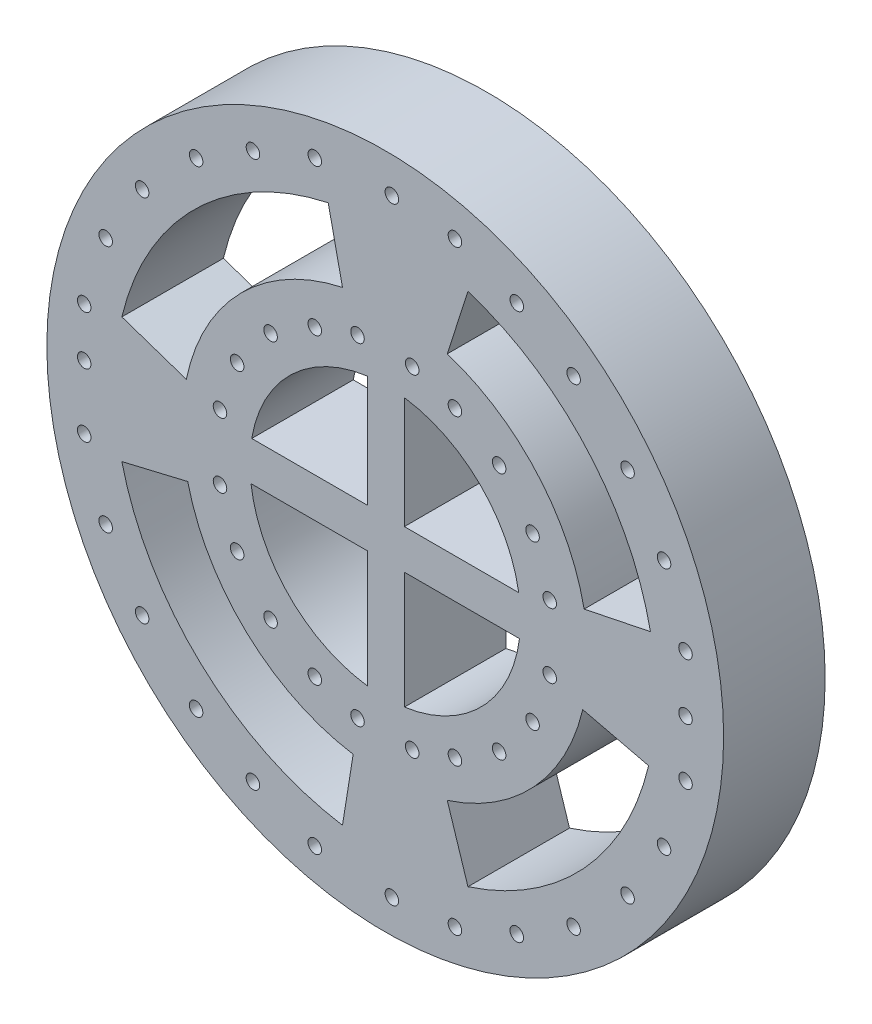
SolidWorks part; units mm, degrees
ref_plane "Front Plane" through (0, 0, 0) normal (0, 0, 1) x (1, 0, 0)
ref_plane "Top Plane" through (0, 0, 0) normal (0, 1, 0) x (1, 0, 0)
ref_plane "Right Plane" through (0, 0, 0) normal (1, 0, 0) x (0, 0, -1)
sketch "Sketch1" plane through (0, 0, 0) normal (0, 0, 1) x (1, 0, 0)
  line L0 (-26.585, -3.3326) -> (-26.585, 40.517)
  line L1 (-40.3947, -3.4074) -> (-40.3947, 40.517)
  line L2 (65.0807, 23.4507) -> (40.3699, 29.3275)
  line L3 (65.7686, 67.3569) -> (40.8858, 62.2571)
  line L4 (-10.4829, 119.5147) -> (-2.723, 143.7003)
  line L5 (-107.8949, 29.3275) -> (-132.6057, 23.4507)
  line L6 (16.3433, 55.3276) -> (-26.585, 55.3276)
  line L7 (-49.8085, -53.3671) -> (-45.797, -28.2859)
  line L8 (-2.723, -49.7847) -> (-10.4829, -25.5991)
  line L9 (-108.4108, 62.2571) -> (-132.6057, 70.4649)
  line L10 (-49.8085, 121.4492) -> (-55.1572, 146.2796)
  line L11 (-84.1525, 40.517) -> (-40.3947, 40.517)
  line L12 (-26.585, 40.517) -> (16.6276, 40.517)
  line L13 (-40.3947, 55.3276) -> (-83.8682, 55.3276)
  line L14 (-26.585, 55.3276) -> (-26.585, 97.2482)
  line L15 (-40.3947, 55.3276) -> (-40.3947, 97.323)
  circle A0 centre (-33.7625, 46.9578) radius 127
  arc A1 (65.7686, 67.3569) -> (-2.723, 143.7003) centre (-33.7625, 46.9578) ccw
  arc A2 (40.8858, 62.2571) -> (-10.4829, 119.5147) centre (-33.7625, 46.9578) ccw
  arc A3 (-84.1525, 40.517) -> (-40.3947, -3.4074) centre (-33.7625, 46.9578) ccw
  arc A4 (-10.4829, -25.5991) -> (40.3699, 29.3275) centre (-33.7625, 46.9578) ccw
  arc A5 (-2.723, -49.7847) -> (65.0807, 23.4507) centre (-33.7625, 46.9578) ccw
  arc A6 (-107.8949, 29.3275) -> (-45.797, -28.2859) centre (-33.7625, 46.9578) ccw
  arc A7 (-132.6057, 23.4507) -> (-49.8085, -53.3671) centre (-33.7625, 46.9578) ccw
  arc A8 (-49.8085, 121.4492) -> (-108.4108, 62.2571) centre (-33.7625, 46.9578) ccw
  arc A9 (-55.1572, 146.2796) -> (-132.6057, 70.4649) centre (-33.7625, 46.9578) ccw
  arc A10 (16.3433, 55.3276) -> (-26.585, 97.2482) centre (-33.7625, 46.9578) ccw
  arc A11 (-26.585, -3.3326) -> (16.6276, 40.517) centre (-33.7625, 46.9578) ccw
  arc A12 (-40.3947, 97.323) -> (-83.8682, 55.3276) centre (-33.7625, 46.9578) ccw
  dimension "D2" = 25.4
  dimension "D3" = 25.4
  dimension "D4" = 25.4
  dimension "D6" = 24.7108
extrude "Boss-Extrude1" add sketch "Sketch1" along normal blind 38.1
sketch "Sketch2" plane through (0, 0, 0) normal (0, 0, -1) x (-1, 0, 0)
  line L0 (138.5194, 26.6409) -> (103.5457, 33.4238)
  line L1 (138.5194, 67.2747) -> (104.2574, 56.0867)
  line L2 (46.1082, -59.0345) -> (41.9865, -23.6484)
  line L3 (4.9215, -55.7796) -> (14.5502, -21.4802)
  line L4 (-70.9944, 26.6409) -> (-36.0208, 33.4238)
  line L5 (-71.4489, 64.7719) -> (-36.3235, 58.8246)
  line L6 (46.1082, 116.9611) -> (52.2956, 152.0449)
  line L7 (14.5502, 115.3958) -> (4.9215, 149.6952)
  circle A0 centre (33.7625, 46.9578) radius 121.8252
  arc A1 (138.5194, 67.2747) -> (52.2956, 152.0449) centre (33.7625, 46.9578) ccw
  arc A2 (104.2574, 56.0867) -> (46.1082, 116.9611) centre (33.7625, 46.9578) ccw
  circle A3 centre (33.7625, 46.9578) radius 55.9484
  arc A4 (41.9865, -23.6484) -> (103.5457, 33.4238) centre (33.7625, 46.9578) ccw
  arc A5 (46.1082, -59.0345) -> (138.5194, 26.6409) centre (33.7625, 46.9578) ccw
  arc A6 (-36.0208, 33.4238) -> (14.5502, -21.4802) centre (33.7625, 46.9578) ccw
  arc A7 (-70.9944, 26.6409) -> (4.9215, -55.7796) centre (33.7625, 46.9578) ccw
  arc A8 (14.5502, 115.3958) -> (-36.3235, 58.8246) centre (33.7625, 46.9578) ccw
  arc A9 (4.9215, 149.6952) -> (-71.4489, 64.7719) centre (33.7625, 46.9578) ccw
extrude "Cut-Extrude1" cut sketch "Sketch2" against normal blind 31.75
sketch "Sketch4" plane through (0, 0, 31.75) normal (0, 0, -1) x (-1, 0, 0)
  circle A0 centre (31.2813, -67.5054) radius 2.54
  circle A1 centre (60.2053, -65.2934) radius 2.54
  circle A2 centre (83.4133, -56.0022) radius 2.54
  circle A3 centre (104.7478, -42.9514) radius 2.54
  circle A4 centre (124.9962, -22.689) radius 2.54
  circle A5 centre (138.6819, 0) radius 2.54
  circle A6 centre (146.7436, 25.4359) radius 2.54
  circle A7 centre (146.7436, 49.2593) radius 2.54
  circle A8 centre (-27.9586, 34.3475) radius 2.54
  circle A9 centre (44.1691, -15.7373) radius 2.54
  circle A10 centre (60.2053, -10.2545) radius 2.54
  circle A11 centre (76.7933, 0) radius 2.54
  circle A12 centre (89.3387, 15.902) radius 2.54
  circle A13 centre (95.7753, 34.3475) radius 2.54
  circle A14 centre (-21.5219, 15.902) radius 2.54
  circle A15 centre (-8.9765, 0) radius 2.54
  circle A16 centre (7.6115, -10.2545) radius 2.54
  circle A17 centre (23.6477, -15.7373) radius 2.54
  circle A18 centre (-78.9268, 46.5261) radius 2.54
  circle A19 centre (-78.9268, 25.4359) radius 2.54
  circle A20 centre (-70.8651, 0) radius 2.54
  circle A21 centre (-57.1794, -22.689) radius 2.54
  circle A22 centre (-36.931, -42.9514) radius 2.54
  circle A23 centre (-15.5965, -56.0022) radius 2.54
  circle A24 centre (7.6115, -65.2934) radius 2.54
  circle A25 centre (95.7753, 58.7048) radius 2.54
  circle A26 centre (-27.9586, 58.7048) radius 2.54
  circle A27 centre (-78.9268, 67.6164) radius 2.54
  circle A28 centre (7.6115, 158.3457) radius 2.54
  circle A29 centre (-15.5965, 149.0545) radius 2.54
  circle A30 centre (-36.931, 136.0037) radius 2.54
  circle A31 centre (-57.1794, 115.7413) radius 2.54
  circle A32 centre (-70.8651, 93.0523) radius 2.54
  circle A33 centre (23.6477, 108.7896) radius 2.54
  circle A34 centre (7.6115, 103.3068) radius 2.54
  circle A35 centre (-8.9765, 93.0523) radius 2.54
  circle A36 centre (-21.5219, 77.1503) radius 2.54
  circle A37 centre (89.3387, 77.1503) radius 2.54
  circle A38 centre (76.7933, 93.0523) radius 2.54
  circle A39 centre (60.2053, 103.3068) radius 2.54
  circle A40 centre (44.1691, 108.7896) radius 2.54
  circle A41 centre (146.7436, 67.6164) radius 2.54
  circle A42 centre (138.6819, 93.0523) radius 2.54
  circle A43 centre (124.9962, 115.7413) radius 2.54
  circle A44 centre (104.7478, 136.0037) radius 2.54
  circle A45 centre (83.4133, 149.0545) radius 2.54
  circle A46 centre (60.2053, 158.3457) radius 2.54
  circle A47 centre (31.2813, 160.5577) radius 2.54
  point P38 (0, 0)
  point P52 (0, 0)
  point P98 (0, 0)
  dimension "D1" = 5.08
extrude "Cut-Extrude3" cut sketch "Sketch4" against normal blind 25.4
